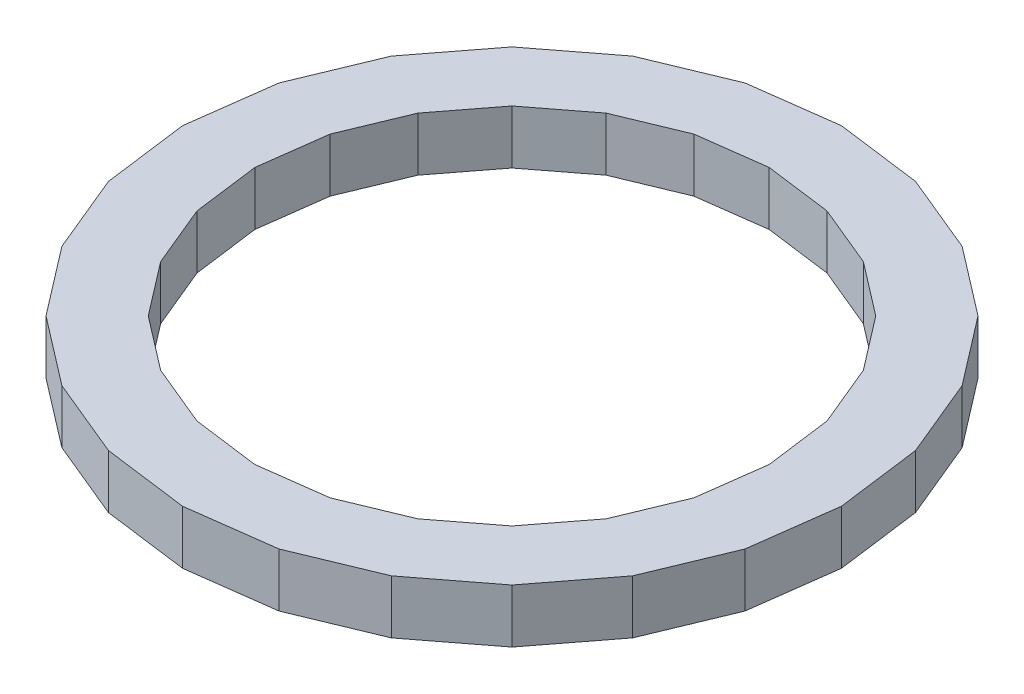
SolidWorks part; units mm, degrees
ref_plane "Front Plane" through (0, 0, 0) normal (0, 0, 1) x (1, 0, 0)
ref_plane "Top Plane" through (0, 0, 0) normal (0, 1, 0) x (1, 0, 0)
ref_plane "Right Plane" through (0, 0, 0) normal (1, 0, 0) x (0, 0, -1)
sketch "Sketch1" plane through (0, 0, 0) normal (0, 1, 0) x (1, 0, 0)
  line L0 (0, 0) -> (-91.139, 0) construction
  line L1 (-91.139, 0) -> (-88.0335, -23.5885)
  line L2 (-88.0335, -23.5885) -> (-78.9287, -45.5695)
  line L3 (-78.9287, -45.5695) -> (-64.445, -64.445)
  line L4 (-64.445, -64.445) -> (-45.5695, -78.9287)
  line L5 (-45.5695, -78.9287) -> (-23.5885, -88.0335)
  line L6 (-23.5885, -88.0335) -> (0, -91.139)
  line L7 (0, -91.139) -> (23.5885, -88.0335)
  line L8 (23.5885, -88.0335) -> (45.5695, -78.9287)
  line L9 (45.5695, -78.9287) -> (64.445, -64.445)
  line L10 (64.445, -64.445) -> (78.9287, -45.5695)
  line L11 (78.9287, -45.5695) -> (88.0335, -23.5885)
  line L12 (88.0335, -23.5885) -> (91.139, 0)
  line L13 (91.139, 0) -> (88.0335, 23.5885)
  line L14 (88.0335, 23.5885) -> (78.9287, 45.5695)
  line L15 (78.9287, 45.5695) -> (64.445, 64.445)
  line L16 (64.445, 64.445) -> (45.5695, 78.9287)
  line L17 (45.5695, 78.9287) -> (23.5885, 88.0335)
  line L18 (23.5885, 88.0335) -> (0, 91.139)
  line L19 (0, 91.139) -> (-23.5885, 88.0335)
  line L20 (-23.5885, 88.0335) -> (-45.5695, 78.9287)
  line L21 (-45.5695, 78.9287) -> (-64.445, 64.445)
  line L22 (-64.445, 64.445) -> (-78.9287, 45.5695)
  line L23 (-78.9287, 45.5695) -> (-88.0335, 23.5885)
  line L24 (-88.0335, 23.5885) -> (-91.139, 0)
  line L25 (-116.7582, 0) -> (-112.7797, -30.2192)
  line L26 (-112.7797, -30.2192) -> (-101.1155, -58.3791)
  line L27 (-101.1155, -58.3791) -> (-82.5605, -82.5605)
  line L28 (-82.5605, -82.5605) -> (-58.3791, -101.1155)
  line L29 (-58.3791, -101.1155) -> (-30.2192, -112.7797)
  line L30 (-30.2192, -112.7797) -> (0, -116.7582)
  line L31 (0, -116.7582) -> (30.2192, -112.7797)
  line L32 (30.2192, -112.7797) -> (58.3791, -101.1155)
  line L33 (58.3791, -101.1155) -> (82.5605, -82.5605)
  line L34 (82.5605, -82.5605) -> (101.1155, -58.3791)
  line L35 (101.1155, -58.3791) -> (112.7797, -30.2192)
  line L36 (112.7797, -30.2192) -> (116.7582, 0)
  line L37 (116.7582, 0) -> (112.7797, 30.2192)
  line L38 (112.7797, 30.2192) -> (101.1155, 58.3791)
  line L39 (101.1155, 58.3791) -> (82.5605, 82.5605)
  line L40 (82.5605, 82.5605) -> (58.3791, 101.1155)
  line L41 (58.3791, 101.1155) -> (30.2192, 112.7797)
  line L42 (30.2192, 112.7797) -> (0, 116.7582)
  line L43 (0, 116.7582) -> (-30.2192, 112.7797)
  line L44 (-30.2192, 112.7797) -> (-58.3791, 101.1155)
  line L45 (-58.3791, 101.1155) -> (-82.5605, 82.5605)
  line L46 (-82.5605, 82.5605) -> (-101.1155, 58.3791)
  line L47 (-101.1155, 58.3791) -> (-112.7797, 30.2192)
  line L48 (-112.7797, 30.2192) -> (-116.7582, 0)
  line L49 (-116.7582, 0) -> (-91.139, 0) construction
  circle A0 centre (0, 0) radius 90.3593 construction
  circle A1 centre (0, 0) radius 115.7593 construction
  dimension "D1" = 25.4
  dimension "D2" = 30.48
  dimension "D3" = 82.5
extrude "Boss-Extrude1" add sketch "Sketch1" along normal blind 19.05
